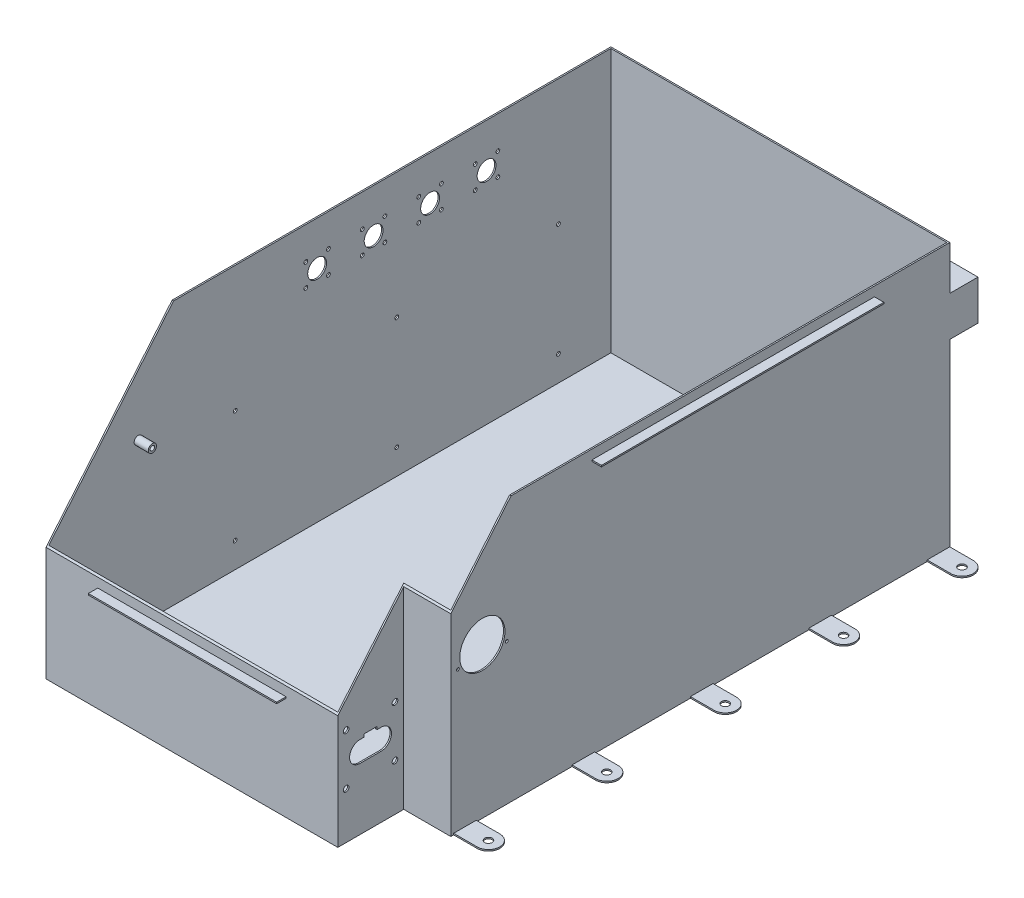
SolidWorks part; units mm, degrees
ref_plane "Front Plane" through (0, 0, 0) normal (0, 0, 1) x (1, 0, 0)
ref_plane "Top Plane" through (0, 0, 0) normal (0, 1, 0) x (1, 0, 0)
ref_plane "Right Plane" through (0, 0, 0) normal (1, 0, 0) x (0, 0, -1)
sketch "Sketch1" plane through (0, 0, 0) normal (0, 1, 0) x (1, 0, 0)
  line L1 (-180, 237.8263) -> (180, 237.8263)
  line L2 (-180, 237.8263) -> (-180, -362.1737)
  line L3 (-180, -362.1737) -> (130, -362.1737)
  line L4 (180, 237.8263) -> (180, -292.1737)
  line L6 (180, -292.1737) -> (130, -292.1737)
  line L7 (130, -292.1737) -> (130, -362.1737)
  line L8 (0, -55) -> (0, 55) construction
  point P1 (0, 237.8263)
  dimension "D1" = 600
  dimension "D2" = 360
  dimension "D5" = 70
  dimension "D6" = 50
extrude "Boss-Extrude1" add sketch "Sketch1" along normal blind 1.5
sketch "Sketch2" plane through (0, 1.5, 0) normal (0, 1, 0) x (1, 0, 0)
  line L60 (-178.5, 236.3263) -> (-178.5, -360.6737)
  line L61 (-178.5, -360.6737) -> (128.5, -360.6737)
  line L62 (128.5, -360.6737) -> (128.5, -290.6737)
  line L63 (128.5, -290.6737) -> (178.5, -290.6737)
  line L64 (178.5, -290.6737) -> (178.5, 236.3263)
  line L65 (178.5, 236.3263) -> (-178.5, 236.3263)
  line L66 (-180, 237.8263) -> (-180, -362.1737)
  line L67 (-180, -362.1737) -> (130, -362.1737)
  line L68 (130, -362.1737) -> (130, -292.1737)
  line L69 (130, -292.1737) -> (180, -292.1737)
  line L70 (180, -292.1737) -> (180, 237.8263)
  line L71 (180, 237.8263) -> (-180, 237.8263)
  line L72 (-180, 237.8263) -> (-180, -362.1737)
  line L73 (-180, -362.1737) -> (130, -362.1737)
  line L74 (130, -362.1737) -> (130, -292.1737)
  line L75 (130, -292.1737) -> (180, -292.1737)
  line L76 (180, -292.1737) -> (180, 237.8263)
  line L77 (180, 237.8263) -> (-180, 237.8263)
  dimension "D1" = 0
  dimension "D2" = 1.5
extrude "Boss-Extrude2" add sketch "Sketch2" along normal blind 280
sketch "Sketch3" plane through (-180, 0, 0) normal (-1, 0, 0) x (0, 0, 1)
  line L3 (362.1737, 281.5) -> (362.1737, 0) construction
  line L4 (362.1737, 121.1176) -> (228.1952, 281.5)
  line L6 (-237.8263, 281.5) -> (362.1737, 281.5) construction
  line L9 (362.1737, 281.5) -> (362.1737, 121.1176)
  line L10 (228.1952, 281.5) -> (362.1737, 281.5)
sketch "Sketch4" plane through (0, 0, -237.8263) normal (0, 0, -1) x (-1, 0, 0)
  line L0 (-180, 281.5) -> (-180, 0) construction
  line L1 (-180, 234.6761) -> (180, 234.6761)
  line L2 (-180, 234.6761) -> (-180, 192.2905)
  line L3 (-180, 192.2905) -> (180, 192.2905)
  line L4 (180, 234.6761) -> (180, 192.2905)
  line L5 (180, 281.5) -> (180, 0) construction
extrude "Boss-Extrude3" add sketch "Sketch4" along normal blind 30
extrude "Cut-Extrude1" cut sketch "Sketch3" against normal through all both and the other way through all
sketch "Sketch5" plane through (-180, 0, 0) normal (-1, 0, 0) x (0, 0, 1)
  line L0 (-116.3263, 223.1259) -> (-116.3263, 247.1259) construction
  line L5 (-116.3263, 223.1259) -> (-92.3263, 223.1259) construction
  line L6 (-116.3263, 247.1259) -> (-92.3263, 247.1259) construction
  line L7 (-92.3263, 223.1259) -> (-92.3263, 247.1259) construction
  line L8 (-116.3263, 223.1259) -> (-92.3263, 247.1259) construction
  line L9 (-116.3263, 247.1259) -> (-92.3263, 223.1259) construction
  line L10 (-56.3263, 223.1259) -> (-56.3263, 247.1259) construction
  line L11 (-56.3263, 223.1259) -> (-32.3263, 223.1259) construction
  line L12 (-56.3263, 247.1259) -> (-32.3263, 247.1259) construction
  line L13 (-32.3263, 223.1259) -> (-32.3263, 247.1259) construction
  line L14 (-56.3263, 223.1259) -> (-32.3263, 247.1259) construction
  line L15 (-56.3263, 247.1259) -> (-32.3263, 223.1259) construction
  line L16 (3.6737, 223.1259) -> (3.6737, 247.1259) construction
  line L17 (3.6737, 223.1259) -> (27.6737, 223.1259) construction
  line L18 (3.6737, 247.1259) -> (27.6737, 247.1259) construction
  line L19 (27.6737, 223.1259) -> (27.6737, 247.1259) construction
  line L20 (3.6737, 223.1259) -> (27.6737, 247.1259) construction
  line L21 (3.6737, 247.1259) -> (27.6737, 223.1259) construction
  line L22 (63.6737, 223.1259) -> (63.6737, 247.1259) construction
  line L23 (63.6737, 223.1259) -> (87.6737, 223.1259) construction
  line L24 (63.6737, 247.1259) -> (87.6737, 247.1259) construction
  line L25 (87.6737, 223.1259) -> (87.6737, 247.1259) construction
  line L26 (63.6737, 223.1259) -> (87.6737, 247.1259) construction
  line L27 (63.6737, 247.1259) -> (87.6737, 223.1259) construction
  line L28 (-236.3263, 281.5) -> (-236.3263, 1.5) construction
  circle A0 centre (-116.3263, 247.1259) radius 2
  circle A1 centre (-116.3263, 223.1259) radius 2
  circle A2 centre (-92.3263, 223.1259) radius 2
  circle A3 centre (-92.3263, 247.1259) radius 2
  circle A4 centre (-104.3263, 235.1259) radius 10
  circle A5 centre (-56.3263, 247.1259) radius 2
  circle A6 centre (-56.3263, 223.1259) radius 2
  circle A7 centre (-32.3263, 223.1259) radius 2
  circle A8 centre (-32.3263, 247.1259) radius 2
  circle A9 centre (-44.3263, 235.1259) radius 10
  circle A10 centre (3.6737, 247.1259) radius 2
  circle A11 centre (3.6737, 223.1259) radius 2
  circle A12 centre (27.6737, 223.1259) radius 2
  circle A13 centre (27.6737, 247.1259) radius 2
  circle A14 centre (15.6737, 235.1259) radius 10
  circle A15 centre (63.6737, 247.1259) radius 2
  circle A16 centre (63.6737, 223.1259) radius 2
  circle A17 centre (87.6737, 223.1259) radius 2
  circle A18 centre (87.6737, 247.1259) radius 2
  circle A19 centre (75.6737, 235.1259) radius 10
  point P9 (-104.3263, 235.1259)
  point P24 (-44.3263, 235.1259)
  point P38 (15.6737, 235.1259)
  point P52 (75.6737, 235.1259)
  dimension "D2" = 20
  dimension "D5" = 4
  dimension "D1" = 24
  dimension "D3" = 24
  dimension "D4" = 24
  dimension "D7" = 120
  dimension "D6" = 4
sketch "Sketch6" plane through (-178.5, 0, 0) normal (1, 0, 0) x (0, 0, -1)
  arc A0 (151.1392, 167.4539) -> (156.7272, 167.4539) centre (153.9332, 167.4539) ccw construction
  arc A1 (-68.8756, 167.4539) -> (-63.2876, 167.4539) centre (-66.0816, 167.4539) ccw construction
  arc A2 (-178.883, 167.4539) -> (-173.295, 167.4539) centre (-176.089, 167.4539) ccw construction
  arc A3 (151.1392, 167.4539) -> (156.7272, 167.4539) centre (153.9332, 167.4539) ccw
  arc A4 (-68.8756, 167.4539) -> (-63.2876, 167.4539) centre (-66.0816, 167.4539) ccw
  arc A5 (-178.883, 167.4539) -> (-173.295, 167.4539) centre (-176.089, 167.4539) ccw
  circle A6 centre (-176.089, 167.4539) radius 2.794
  circle A7 centre (-176.089, 167.4539) radius 4.5
  circle A8 centre (-64.4633, 167.4539) radius 4.5
  circle A9 centre (-64.4633, 167.4539) radius 2.794
  circle A10 centre (155.5515, 167.4539) radius 2.794
  circle A11 centre (155.5515, 167.4539) radius 4.5
  dimension "D1" = 9
extrude "Boss-Extrude4" [suppressed] add sketch "Sketch6" along normal blind 50 contours A4 A9 | A8 | A7 | A6 | A11 | A10
sketch "Sketch8" plane through (-178.5, 0, 0) normal (1, 0, 0) x (0, 0, -1)
  line L0 (236.3263, 1.5) -> (-360.6737, 1.5) construction
  line L1 (-360.6737, 122.9132) -> (-360.6737, 1.5) construction
  circle A0 centre (-265.6737, 172.2) radius 2.39
  circle A1 centre (-265.6737, 172.2) radius 4.39
  circle A2 centre (-265.6737, 16.5) radius 2.39
  circle A3 centre (-265.6737, 16.5) radius 4.39
  dimension "D3" = 4.78
  dimension "D4" = 2
  dimension "D1" = 155.7
  dimension "D2" = 15
  dimension "D5" = 95
extrude "Boss-Extrude5" add sketch "Sketch8" along normal blind 15
sketch "Sketch10" plane through (128.5, 0, 0) normal (-1, 0, 0) x (0, 0, 1)
  line L0 (316.1737, 86.5) -> (321.4237, 86.5) construction
  line L1 (316.1737, 66.5) -> (338.6737, 66.5) construction
  line L2 (338.6737, 76.5) -> (316.1737, 76.5) construction
  line L3 (360.6737, 1.5) -> (290.6737, 1.5) construction
  line L5 (321.4237, 86.5) -> (321.4237, 89.5) construction
  line L6 (321.4237, 89.5) -> (333.4237, 89.5) construction
  line L7 (333.4237, 86.5) -> (333.4237, 89.5) construction
  line L8 (360.6737, 122.9132) -> (360.6737, 1.5) construction
  line L9 (333.4237, 86.5) -> (338.6737, 86.5) construction
  line L10 (320.4237, 90.5) -> (334.4237, 90.5)
  line L11 (334.4237, 87.5) -> (334.4237, 90.5)
  line L12 (334.4237, 87.5) -> (338.6737, 87.5)
  line L13 (316.1737, 65.5) -> (338.6737, 65.5)
  line L14 (316.1737, 87.5) -> (320.4237, 87.5)
  line L15 (320.4237, 87.5) -> (320.4237, 90.5)
  line L17 (301.4737, 49.55) -> (353.3737, 49.55) construction
  line L18 (301.4737, 49.55) -> (301.4737, 103.45) construction
  line L19 (301.4737, 103.45) -> (353.3737, 103.45) construction
  line L20 (353.3737, 49.55) -> (353.3737, 103.45) construction
  line L21 (301.4737, 49.55) -> (353.3737, 103.45) construction
  line L22 (301.4737, 103.45) -> (353.3737, 49.55) construction
  arc A0 (316.1737, 86.5) -> (316.1737, 66.5) centre (316.1737, 76.5) ccw construction
  arc A1 (338.6737, 66.5) -> (338.6737, 86.5) centre (338.6737, 76.5) ccw construction
  arc A2 (338.6737, 65.5) -> (338.6737, 87.5) centre (338.6737, 76.5) ccw
  arc A3 (316.1737, 87.5) -> (316.1737, 65.5) centre (316.1737, 76.5) ccw
  circle A4 centre (301.4737, 103.45) radius 3
  circle A5 centre (353.3737, 103.45) radius 3
  circle A6 centre (301.4737, 49.55) radius 3
  circle A7 centre (353.3737, 49.55) radius 3
  point P12 (327.4237, 89.5)
  point P13 (327.4237, 76.5)
  point P26 (327.4237, 76.5)
  dimension "D1" = 65
  dimension "D2" = 22.5
  dimension "D6" = 20
  dimension "D10" = 6
  dimension "D3" = 22
  dimension "D4" = 12
  dimension "D5" = 3
  dimension "D8" = 51.9
  dimension "D9" = 53.9
  dimension "D7" = 1
extrude "Cut-Extrude2" cut sketch "Sketch10" against normal up to surface (1.5 mm away)
sketch "Sketch11" plane through (128.5, 0, 0) normal (-1, 0, 0) x (0, 0, 1)
  line L0 (298.4737, 103.43) -> (298.4737, 49.53) construction
  line L13 (316.1737, 66.5) -> (338.6737, 66.5) construction
  line L14 (316.1737, 86.5) -> (321.4237, 86.5) construction
  line L15 (316.1737, 66.5) -> (338.6737, 66.5)
  line L19 (316.1737, 86.5) -> (318.4237, 86.5)
  line L20 (334.4237, 90.5) -> (320.4237, 90.5)
  line L21 (334.4237, 90.5) -> (320.4237, 90.5)
  line L22 (334.4237, 87.5) -> (334.4237, 90.5)
  line L23 (334.4237, 87.5) -> (334.4237, 90.5)
  line L28 (330.4237, 86.5) -> (321.4237, 86.5)
  line L29 (316.2509, 66) -> (338.7144, 66)
  line L30 (330.9237, 86) -> (320.7529, 86)
  line L31 (330.9237, 86) -> (330.9237, 91)
  line L32 (330.9237, 91) -> (317.9237, 91)
  line L33 (317.9237, 91) -> (317.9237, 87)
  line L34 (316.2509, 87) -> (317.9237, 87)
  line L36 (298.4737, 103.43) -> (350.3737, 103.43) construction
  line L43 (334.4237, 90.5) -> (320.4237, 90.5)
  line L44 (334.4237, 90.5) -> (320.4237, 90.5)
  line L45 (334.4237, 87.5) -> (334.4237, 90.5)
  line L46 (334.4237, 87.5) -> (334.4237, 90.5)
  line L47 (338.6737, 87.5) -> (334.4237, 87.5)
  line L48 (338.6737, 87.5) -> (334.4237, 87.5)
  line L49 (316.1737, 65.5) -> (338.6737, 65.5)
  line L50 (316.1737, 65.5) -> (338.6737, 65.5)
  line L51 (320.4237, 87.5) -> (316.1737, 87.5)
  line L52 (320.4237, 87.5) -> (316.1737, 87.5)
  line L53 (320.4237, 90.5) -> (320.4237, 87.5)
  line L54 (320.4237, 90.5) -> (320.4237, 87.5)
  line L55 (334.4237, 90.5) -> (320.4237, 90.5)
  line L56 (334.4237, 90.5) -> (320.4237, 90.5)
  line L57 (334.4237, 87.5) -> (334.4237, 90.5)
  line L58 (334.4237, 87.5) -> (334.4237, 90.5)
  line L59 (338.6737, 87.5) -> (334.4237, 87.5)
  line L60 (338.6737, 87.5) -> (334.4237, 87.5)
  line L61 (316.1737, 65.5) -> (338.6737, 65.5)
  line L62 (316.1737, 65.5) -> (338.6737, 65.5)
  line L63 (320.4237, 87.5) -> (316.1737, 87.5)
  line L64 (320.4237, 87.5) -> (316.1737, 87.5)
  line L65 (320.4237, 90.5) -> (320.4237, 87.5)
  line L66 (320.4237, 90.5) -> (320.4237, 87.5)
  line L67 (330.4237, 86.5) -> (330.4237, 90.5) construction
  line L68 (330.4237, 90.5) -> (318.4237, 90.5) construction
  line L69 (318.4237, 90.5) -> (318.4237, 86.5) construction
  line L70 (338.6737, 87.5) -> (334.4237, 87.5)
  line L71 (338.6737, 87.5) -> (334.4237, 87.5)
  line L72 (316.1737, 65.5) -> (338.6737, 65.5)
  line L73 (316.1737, 65.5) -> (338.6737, 65.5)
  line L74 (320.4237, 87.5) -> (316.1737, 87.5)
  line L75 (320.4237, 87.5) -> (316.1737, 87.5)
  line L76 (320.4237, 90.5) -> (320.4237, 87.5)
  line L77 (320.4237, 90.5) -> (320.4237, 87.5)
  arc A4 (338.7144, 66) -> (320.7529, 86) centre (336.1498, 81.7622) ccw
  arc A5 (338.6737, 65.5) -> (338.6737, 87.5) centre (338.6737, 76.5) ccw
  arc A7 (338.6737, 65.5) -> (338.6737, 87.5) centre (338.6737, 76.5) ccw
  arc A9 (316.2509, 87) -> (316.2509, 66) centre (312.9721, 76.5) ccw
  circle A10 centre (298.4737, 103.43) radius 3
  circle A11 centre (298.4737, 49.53) radius 3
  circle A12 centre (350.3737, 103.43) radius 3
  circle A13 centre (350.3737, 49.53) radius 3
  arc A16 (338.6737, 66.5) -> (321.4237, 86.5) centre (336.1498, 81.7622) ccw construction
  arc A17 (338.6737, 65.5) -> (338.6737, 87.5) centre (338.6737, 76.5) ccw
  arc A18 (316.1737, 87.5) -> (316.1737, 65.5) centre (316.1737, 76.5) ccw
  arc A19 (316.1737, 87.5) -> (316.1737, 65.5) centre (316.1737, 76.5) ccw
  arc A20 (316.1737, 86.5) -> (316.1737, 66.5) centre (312.9721, 76.5) ccw construction
  arc A21 (338.6737, 65.5) -> (338.6737, 87.5) centre (338.6737, 76.5) ccw
  arc A22 (316.1737, 87.5) -> (316.1737, 65.5) centre (316.1737, 76.5) ccw
  arc A23 (316.1737, 87.5) -> (316.1737, 65.5) centre (316.1737, 76.5) ccw
  arc A24 (338.6737, 65.5) -> (338.6737, 87.5) centre (338.6737, 76.5) ccw
  arc A25 (338.6737, 65.5) -> (338.6737, 87.5) centre (338.6737, 76.5) ccw
  arc A26 (316.1737, 87.5) -> (316.1737, 65.5) centre (316.1737, 76.5) ccw
  arc A27 (316.1737, 87.5) -> (316.1737, 65.5) centre (316.1737, 76.5) ccw
  point P33 (324.4237, 103.43)
  dimension "D5" = 6
  dimension "D6" = 51.9
  dimension "D7" = 53.9
  dimension "D1" = 0
  dimension "D2" = 0
  dimension "D3" = 0
  dimension "D4" = 0.5
extrude "Cut-Extrude3" [suppressed] cut sketch "Sketch11" against normal through all
sketch "Sketch14" plane through (128.5, 0, 0) normal (-1, 0, 0) x (0, 0, 1)
  line L0 (362.1737, 121.1176) -> (362.1737, 0) construction
  line L1 (362.1737, 0) -> (292.1737, 0) construction
  circle A0 centre (297.2737, 103.43) radius 3
  circle A1 centre (349.1737, 103.43) radius 3
  circle A2 centre (349.1737, 49.53) radius 3
  circle A3 centre (297.2737, 49.53) radius 3
  dimension "D5" = 6
  dimension "D1" = 51.9
  dimension "D2" = 53.9
  dimension "D3" = 13
  dimension "D4" = 103.43
extrude "Cut-Extrude4" [suppressed] cut sketch "Sketch14" against normal up to surface (1.5 mm away)
sketch "Sketch15" plane through (178.5, 0, 0) normal (-1, 0, 0) x (0, 0, 1)
  line L1 (-151.3263, 252.1363) -> (-136.3263, 252.1363)
  line L2 (-151.3263, 252.1363) -> (-151.3263, 250.6363)
  line L3 (-151.3263, 250.6363) -> (-136.3263, 250.6363)
  line L4 (-136.3263, 252.1363) -> (-136.3263, 250.6363)
  line L5 (-236.3263, 281.5) -> (-236.3263, 1.5) construction
  line L6 (126.6737, 252.1363) -> (146.6737, 252.1363)
  line L7 (126.6737, 250.6363) -> (146.6737, 250.6363)
  line L8 (126.6737, 252.1363) -> (126.6737, 250.6363)
  line L9 (146.6737, 252.1363) -> (146.6737, 250.6363)
  dimension "D1" = 1.5
  dimension "D2" = 15
  dimension "D3" = 85
  dimension "D4" = 363
  dimension "D5" = 20
extrude "Boss-Extrude6" add sketch "Sketch15" along normal blind 13
ref_plane "Plane1" through (0, 0, -131.3263) normal (0, 0, -1) x (-1, 0, 0)
sketch "Sketch17" plane through (0, 0, -136.3263) normal (0, 0, 1) x (1, 0, 0)
  line L0 (178.5, 250.6363) -> (178.5, 235.6363)
  line L1 (178.5, 281.5) -> (178.5, 206.7085) construction
  line L2 (178.5, 235.6363) -> (165.5, 250.6363)
  line L3 (165.5, 250.6363) -> (178.5, 250.6363)
  dimension "D1" = 15
extrude "Boss-Extrude7" add sketch "Sketch17" against normal blind 1.5
ref_plane "Plane2" through (0, 0, 126.6737) normal (0, 0, 1) x (1, 0, 0)
sketch "Sketch18" plane through (0, 0, 126.6737) normal (0, 0, 1) x (1, 0, 0)
  line L0 (178.5, 250.6363) -> (178.5, 235.6363)
  line L1 (178.5, 281.5) -> (178.5, 206.7085) construction
  line L2 (178.5, 235.6363) -> (165.5, 250.6363)
  line L3 (165.5, 250.6363) -> (178.5, 250.6363)
  dimension "D1" = 15
extrude "Boss-Extrude8" add sketch "Sketch18" along normal blind 1.5
sketch "Sketch20" plane through (0, 252.1363, 0) normal (0, 1, 0) x (1, 0, 0)
  line L1 (165.5, 151.3263) -> (178.5, 151.3263) construction
  line L2 (165.5, 136.3263) -> (165.5, 151.3263) construction
  line L3 (165.5, -146.6737) -> (178.5, -146.6737) construction
  line L4 (165.5, -146.6737) -> (165.5, -126.6737) construction
  circle A0 centre (173, 144.3263) radius 2.4159
  circle A1 centre (175.5, -139.6737) radius 2
  dimension "D3" = 4
  dimension "D1" = 7
  dimension "D2" = 7.5
  dimension "D4" = 7
  dimension "D5" = 10
extrude "Cut-Extrude5" cut sketch "Sketch20" against normal up to surface (1.5 mm away) up to face at (172, 250.6363, -144.5763)
extrude "Cut-Extrude7" cut sketch "Sketch5" against normal up to surface (1.5 mm away) up to face at (-178.5, 16.5, 261.2837)
sketch "Sketch21" plane through (0, 0, -237.8263) normal (0, 0, -1) x (-1, 0, 0)
  line L0 (-180, 281.5) -> (180, 281.5) construction
  line L1 (-150, 271.5) -> (150, 271.5)
  line L2 (-150, 271.5) -> (-150, 270)
  line L3 (-150, 270) -> (150, 270)
  line L4 (150, 271.5) -> (150, 270)
  point P6 (0, 281.5)
  point P7 (0, 271.5)
  dimension "D1" = 1.5
  dimension "D2" = 300
  dimension "D3" = 10
extrude "Boss-Extrude9" add sketch "Sketch21" along normal blind 10
sketch "Sketch22" plane through (-180, 0, 0) normal (-1, 0, 0) x (0, 0, 1)
  line L0 (-237.8263, 281.5) -> (228.1952, 281.5) construction
  line L1 (-157.8263, 271.5) -> (142.1737, 271.5)
  line L2 (-157.8263, 271.5) -> (-157.8263, 270)
  line L3 (-157.8263, 270) -> (142.1737, 270)
  line L4 (142.1737, 271.5) -> (142.1737, 270)
  line L5 (-237.8263, 281.5) -> (-237.8263, 234.6761) construction
  dimension "D1" = 1.5
  dimension "D2" = 10
  dimension "D3" = 80
  dimension "D4" = 300
extrude "Boss-Extrude10" add sketch "Sketch22" along normal blind 10
ref_plane "Plane3" through (0, 0, -77.8263) normal (0, 0, -1) x (-1, 0, 0)
sketch "Sketch23" plane through (0, 0, -77.8263) normal (0, 0, -1) x (-1, 0, 0)
  line L0 (190, 270) -> (180, 270) construction
  line L1 (190, 270) -> (180, 270)
  line L2 (190, 270) -> (180, 260)
  line L3 (180, 281.5) -> (180, 234.6761) construction
  line L4 (180, 260) -> (180, 270)
  dimension "D1" = 10
extrude "Boss-Extrude11" add sketch "Sketch23" along normal mid plane 1.5
ref_plane "Plane4" through (0, 0, 52.1737) normal (0, 0, 1) x (1, 0, 0)
sketch "Sketch24" plane through (0, 0, 52.1737) normal (0, 0, 1) x (1, 0, 0)
  line L6 (-190, 270) -> (-180, 260)
  line L7 (-180, 260) -> (-180, 270)
  line L8 (-180, 270) -> (-190, 270)
  line L9 (-190, 270) -> (-180, 260)
  line L10 (-180, 260) -> (-180, 270)
  line L11 (-180, 270) -> (-190, 270)
  dimension "D1" = 0
extrude "Boss-Extrude12" add sketch "Sketch24" along normal mid plane 1.5
ref_plane "Plane5" through (100, 0, 0) normal (1, 0, 0) x (0, 0, -1)
sketch "Sketch25" plane through (100, 0, 0) normal (1, 0, 0) x (0, 0, -1)
  line L0 (247.8263, 270) -> (237.8263, 270)
  line L1 (237.8263, 270) -> (237.8263, 260)
  line L2 (237.8263, 281.5) -> (237.8263, 234.6761) construction
  line L3 (237.8263, 260) -> (247.8263, 270)
  dimension "D1" = 10
extrude "Boss-Extrude13" add sketch "Sketch25" along normal mid plane 1.5
ref_plane "Plane6" through (-100, 0, 0) normal (-1, 0, 0) x (0, 0, 1)
sketch "Sketch26" plane through (-100, 0, 0) normal (-1, 0, 0) x (0, 0, 1)
  line L3 (-247.8263, 270) -> (-237.8263, 260)
  line L4 (-237.8263, 260) -> (-237.8263, 270)
  line L5 (-237.8263, 270) -> (-247.8263, 270)
  line L6 (-247.8263, 270) -> (-237.8263, 260)
  line L7 (-237.8263, 260) -> (-237.8263, 270)
  line L8 (-237.8263, 270) -> (-247.8263, 270)
  dimension "D1" = 0
extrude "Boss-Extrude14" add sketch "Sketch26" along normal mid plane 1.5
mirror "Mirror1" about plane through (0, 0, 0) normal (1, 0, 0) of "Boss-Extrude11", "Boss-Extrude12", "Boss-Extrude10"
sketch "Sketch27" plane through (0, 0, 362.1737) normal (0, 0, 1) x (1, 0, 0)
  line L0 (130, 121.1176) -> (-180, 121.1176) construction
  line L1 (-125, 111.1176) -> (75, 111.1176)
  line L2 (-125, 111.1176) -> (-125, 109.6176)
  line L3 (-125, 109.6176) -> (75, 109.6176)
  line L4 (75, 111.1176) -> (75, 109.6176)
  line L5 (130, 121.1176) -> (-180, 121.1176) construction
  point P6 (-25, 121.1176)
  point P7 (-25, 111.1176)
  dimension "D1" = 1.5
  dimension "D2" = 200
  dimension "D3" = 10
extrude "Boss-Extrude15" add sketch "Sketch27" along normal blind 10
ref_plane "Plane7" through (-95, 0, 0) normal (-1, 0, 0) x (0, 0, 1)
sketch "Sketch28" plane through (-95, 0, 0) normal (-1, 0, 0) x (0, 0, 1)
  line L0 (372.1737, 109.6176) -> (362.1737, 109.6176)
  line L1 (362.1737, 109.6176) -> (362.1737, 99.6176)
  line L2 (362.1737, 121.1176) -> (362.1737, 0) construction
  line L3 (362.1737, 99.6176) -> (372.1737, 109.6176)
  dimension "D1" = 10
extrude "Boss-Extrude16" add sketch "Sketch28" along normal mid plane 1.5
ref_plane "Plane8" through (45, 0, 0) normal (1, 0, 0) x (0, 0, -1)
sketch "Sketch29" plane through (45, 0, 0) normal (1, 0, 0) x (0, 0, -1)
  line L3 (-372.1737, 109.6176) -> (-362.1737, 99.6176)
  line L4 (-362.1737, 99.6176) -> (-362.1737, 109.6176)
  line L5 (-362.1737, 109.6176) -> (-372.1737, 109.6176)
  line L6 (-372.1737, 109.6176) -> (-362.1737, 99.6176)
  line L7 (-362.1737, 99.6176) -> (-362.1737, 109.6176)
  line L8 (-362.1737, 109.6176) -> (-372.1737, 109.6176)
  dimension "D1" = 0
extrude "Boss-Extrude17" add sketch "Sketch29" along normal mid plane 1.5
sketch "Sketch30" plane through (180, 0, 0) normal (1, 0, 0) x (0, 0, -1)
  line L1 (-292.1737, 0) -> (237.8263, 0) construction
  line L2 (-292.1737, 204.9129) -> (-292.1737, 0) construction
  circle A0 centre (-258.6737, 160) radius 24
  circle A1 centre (-284.6737, 150) radius 1.5
  circle A2 centre (-232.6737, 150) radius 1.5
  dimension "D1" = 48
  dimension "D2" = 3
  dimension "D3" = 3
  dimension "D4" = 26
  dimension "D5" = 10
  dimension "D6" = 26
  dimension "D7" = 10
  dimension "D8" = 160
  dimension "D9" = 33.5
extrude "Cut-Extrude8" cut sketch "Sketch30" against normal up to surface (1.5 mm away) up to face at (178.5, 246.1363, -141.8263)
sketch "Sketch31" plane through (0, 0, 0) normal (0, -1, 0) x (1, 0, 0)
  line L0 (180, -237.8263) -> (-180, -237.8263) construction
  line L1 (180, -213.8263) -> (205, -213.8263)
  line L2 (180, -213.8263) -> (180, -237.8263)
  line L3 (180, -237.8263) -> (205, -237.8263)
  line L4 (205, -213.8263) -> (205, -237.8263)
  line L64 (180, 228.1952) -> (180, -237.8263) construction
  line L65 (180, -88.0763) -> (205, -88.0763)
  line L66 (180, -88.0763) -> (180, -112.0763)
  line L67 (180, -112.0763) -> (205, -112.0763)
  line L68 (205, -88.0763) -> (205, -112.0763)
  line L69 (180, 37.6737) -> (205, 37.6737)
  line L70 (180, 37.6737) -> (180, 13.6737)
  line L71 (180, 13.6737) -> (205, 13.6737)
  line L72 (205, 37.6737) -> (205, 13.6737)
  line L73 (180, 163.4237) -> (205, 163.4237)
  line L74 (180, 163.4237) -> (180, 139.4237)
  line L75 (180, 139.4237) -> (205, 139.4237)
  line L76 (205, 163.4237) -> (205, 139.4237)
  line L77 (180, 289.1737) -> (205, 289.1737)
  line L78 (180, 289.1737) -> (180, 265.1737)
  line L79 (180, 265.1737) -> (205, 265.1737)
  line L80 (205, 289.1737) -> (205, 265.1737)
  line L81 (-205, 139.4237) -> (-205, 163.4237)
  line L82 (-205, -237.8263) -> (-205, -213.8263)
  line L83 (-180, -112.0763) -> (-180, -88.0763)
  line L84 (-180, -213.8263) -> (-205, -213.8263)
  line L85 (-180, 265.1737) -> (-180, 289.1737)
  line L86 (-180, -112.0763) -> (-205, -112.0763)
  line L87 (-205, -112.0763) -> (-205, -88.0763) construction
  line L88 (-180, 13.6737) -> (-205, 13.6737)
  line L89 (-180, 139.4237) -> (-180, 163.4237)
  line L90 (-180, 37.6737) -> (-205, 37.6737)
  line L91 (-180, 265.1737) -> (-205, 265.1737)
  line L92 (-180, 163.4237) -> (-205, 163.4237)
  line L93 (-180, 13.6737) -> (-180, 37.6737)
  line L94 (-205, 13.6737) -> (-205, 37.6737)
  line L95 (-180, -237.8263) -> (-205, -237.8263)
  line L96 (-205, 265.1737) -> (-205, 289.1737) construction
  line L97 (-180, 289.1737) -> (-205, 289.1737)
  line L98 (-180, -88.0763) -> (-205, -88.0763)
  line L99 (-180, 139.4237) -> (-205, 139.4237)
  line L100 (-180, -237.8263) -> (-180, -213.8263)
  circle A0 centre (205, -225.8263) radius 12
  circle A1 centre (205, -225.8263) radius 4
  circle A30 centre (205, -100.0763) radius 12
  circle A31 centre (205, -100.0763) radius 4
  circle A32 centre (205, 25.6737) radius 12
  circle A33 centre (205, 25.6737) radius 4
  circle A34 centre (205, 151.4237) radius 12
  circle A35 centre (205, 151.4237) radius 4
  circle A36 centre (205, 277.1737) radius 12
  circle A37 centre (205, 277.1737) radius 4
  circle A38 centre (-205, 277.1737) radius 4
  circle A39 centre (-205, 151.4237) radius 12
  circle A40 centre (-205, -225.8263) radius 12
  circle A41 centre (-205, 25.6737) radius 4
  circle A42 centre (-205, 277.1737) radius 12
  circle A43 centre (-205, -100.0763) radius 4
  circle A44 centre (-205, -225.8263) radius 4
  circle A45 centre (-205, 25.6737) radius 12
  circle A46 centre (-205, -100.0763) radius 12
  circle A47 centre (-205, 151.4237) radius 4
  dimension "D3" = 8
  dimension "D8" = 8
  dimension "D1" = 24
  dimension "D2" = 25
  dimension "D5" = 101.75
  dimension "D4" = 5
  dimension "D6" = 24
  dimension "D7" = 25
  dimension "D9" = 101.75
extrude "Boss-Extrude18" add sketch "Sketch31" against normal blind 1.5 separate body
sketch "Sketch33" plane through (-180, 0, 0) normal (-1, 0, 0) x (0, 0, 1)
  line L0 (-237.8263, 192.2905) -> (-237.8263, 0) construction
  line L1 (-237.8263, 0) -> (362.1737, 0) construction
  circle A0 centre (-180.6263, 147.77) radius 2
  circle A1 centre (-180.6263, 28.39) radius 2
  circle A2 centre (-8.9263, 147.77) radius 2
  circle A3 centre (-8.9263, 28.39) radius 2
  circle A4 centre (162.7737, 147.77) radius 2
  circle A5 centre (162.7737, 28.39) radius 2
  dimension "D3" = 4
  dimension "D1" = 57.2
  dimension "D2" = 119.38
  dimension "D4" = 28.39
  dimension "D5" = 3
extrude "Cut-Extrude9" cut sketch "Sketch33" against normal up to surface (1.5 mm away) up to face at (-178.5, 223.1259, 25.6737)
